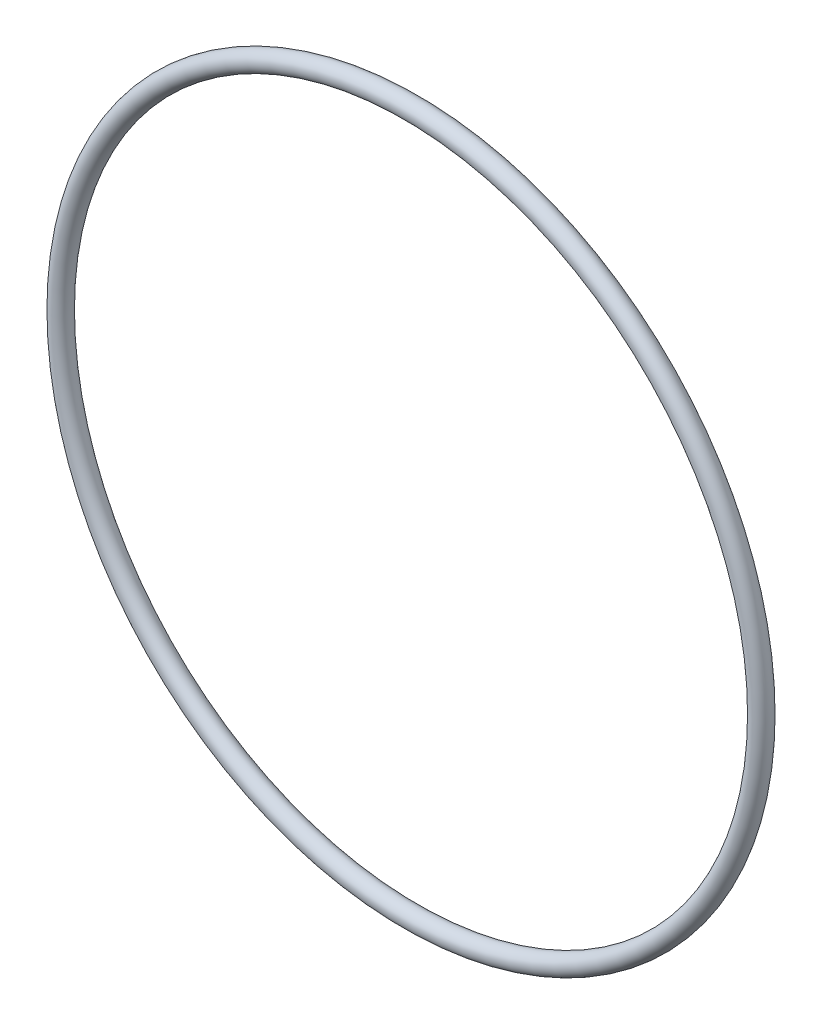
SolidWorks part; units mm, degrees
ref_plane "Front" through (0, 0, 0) normal (0, 0, 1) x (1, 0, 0)
ref_plane "Top" through (0, 0, 0) normal (0, 1, 0) x (1, 0, 0)
ref_plane "Right" through (0, 0, 0) normal (1, 0, 0) x (0, 0, -1)
sketch "Sketch1" plane through (0, 0, 0) normal (1, 0, 0) x (0, -1, 0)
  line L0 (0, -1.7653) -> (0, 1.7653) construction
  line L2 (-71.7639, 0) -> (71.7639, 0) construction
  line L3 (-61.7093, 0) -> (61.7093, 0) construction
  circle A0 centre (63.4746, 0) radius 1.7653
  point P9 (61.7093, 0)
  point P10 (65.2399, 0)
  point P13 (63.4746, 1.7653)
  point P14 (63.4746, -1.7653)
  dimension "Width" = 3.5306
  dimension "ID" = 123.4186
revolve "Revolve1" add sketch "Sketch1" angle 360 about L0
